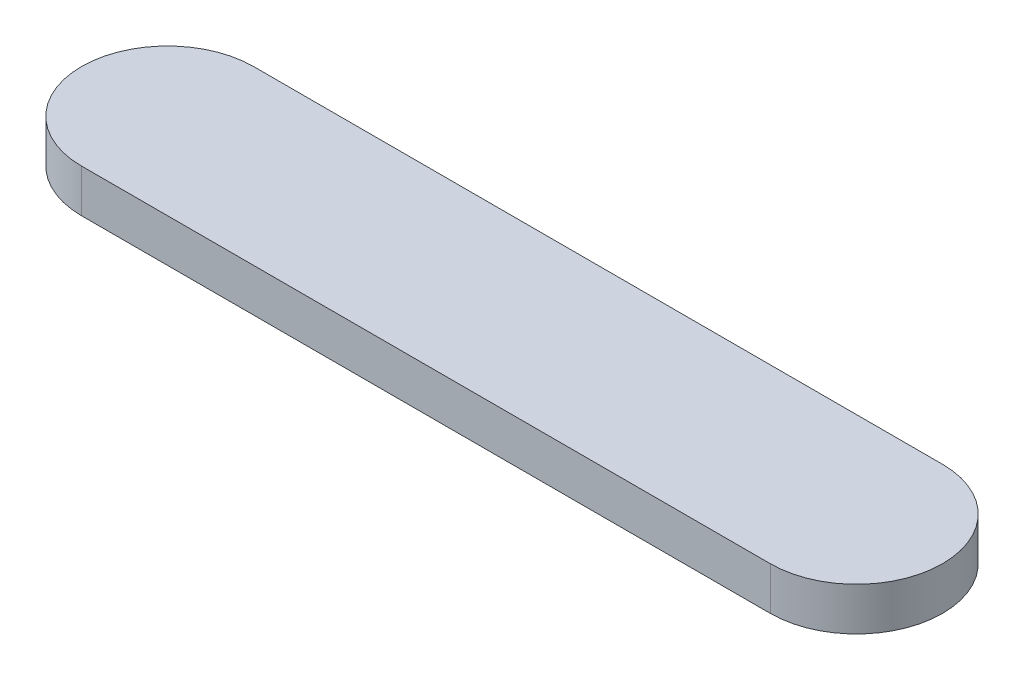
SolidWorks part; units mm, degrees
ref_plane "前视基准面" through (0, 0, 0) normal (0, 0, 1) x (1, 0, 0)
ref_plane "上视基准面" through (0, 0, 0) normal (0, 1, 0) x (1, 0, 0)
ref_plane "右视基准面" through (0, 0, 0) normal (1, 0, 0) x (0, 0, -1)
other "Configuration Table"
sketch "草图1" plane through (0, 0, 0) normal (0, 1, 0) x (1, 0, 0)
  line L0 (0, 0) -> (400, 0) construction
  line L1 (0, 50) -> (400, 50)
  line L2 (0, -50) -> (400, -50)
  arc A0 (0, 50) -> (0, -50) centre (0, 0) ccw
  arc A1 (400, -50) -> (400, 50) centre (400, 0) ccw
  point P3 (200, 0)
  dimension "D1" = 50
  dimension "D2" = 400
extrude "凸台-拉伸1" add sketch "草图1" along normal blind 25
